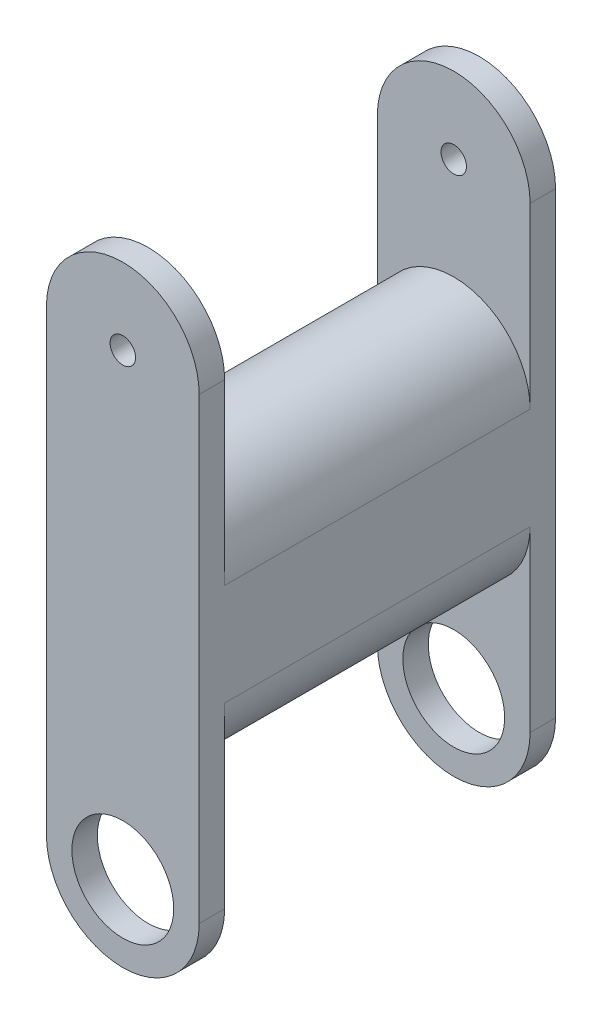
SolidWorks part; units mm, degrees
ref_plane "前视基准面" through (0, 0, 0) normal (0, 0, 1) x (1, 0, 0)
ref_plane "上视基准面" through (0, 0, 0) normal (0, 1, 0) x (1, 0, 0)
ref_plane "右视基准面" through (0, 0, 0) normal (1, 0, 0) x (0, 0, -1)
other "Configuration Table"
sketch "草图1" plane through (0, 0, 0) normal (0, 0, 1) x (1, 0, 0)
  line L0 (0, 0) -> (0, 98.1827) construction
  line L2 (-15, 90) -> (15, 90) construction
  line L3 (-15, 90) -> (-15, 0)
  line L4 (-15, 0) -> (15, 0) construction
  line L5 (15, 90) -> (15, 0)
  arc A0 (-15, 0) -> (15, 0) centre (0, 0) ccw
  arc A1 (15, 90) -> (-15, 90) centre (0, 90) ccw
  circle A2 centre (0, 0) radius 10
  circle A3 centre (0, 90) radius 2.5
  dimension "D3" = 20
  dimension "D4" = 5
  dimension "D1" = 90
  dimension "D2" = 30
extrude "凸台-拉伸1" add sketch "草图1" along normal blind 70
sketch "草图2" plane through (-15, 0, 0) normal (-1, 0, 0) x (0, 0, 1)
  line L0 (35, 108.1134) -> (35, -21.1946) construction
  line L1 (70, 90) -> (70, 0) construction
  line L2 (0, 90) -> (0, 0) construction
  line L4 (5, 20) -> (65, 20)
  line L5 (5, 20) -> (5, -20)
  line L6 (5, -20) -> (65, -20)
  line L7 (65, 20) -> (65, -20)
  line L8 (5, 120) -> (65, 120)
  line L9 (5, 120) -> (5, 70)
  line L10 (5, 70) -> (65, 70)
  line L11 (65, 120) -> (65, 70)
  dimension "D1" = 20
  dimension "D2" = 60
  dimension "D3" = 60
  dimension "D4" = 70
  dimension "D5" = 50
  dimension "D6" = 40
extrude "切除-拉伸1" cut sketch "草图2" against normal blind 70 contours L11 L10 L9 L8 | L6 L7 L4 L5
sketch "草图3" plane through (0, 0, 65) normal (0, 0, -1) x (-1, 0, 0)
  line L0 (0, 0) -> (0, 40) construction
  line L1 (15, 70) -> (15, 55)
  line L2 (-15, 70) -> (-15, 55)
  line L3 (-15, 35) -> (-15, 20)
  line L4 (15, 0) -> (15, 20)
  line L5 (15, 20) -> (-15, 20)
  line L6 (-15, 20) -> (-15, 0)
  line L7 (15, 0) -> (15, 20) construction
  line L8 (15, 20) -> (-15, 20)
  line L9 (-15, 20) -> (-15, 0) construction
  line L10 (-15, 90) -> (-15, 70)
  line L11 (-15, 70) -> (15, 70)
  line L12 (15, 70) -> (15, 90)
  line L13 (-15, 90) -> (-15, 70) construction
  line L14 (-15, 70) -> (15, 70)
  line L15 (15, 70) -> (15, 90) construction
  line L16 (0, 50) -> (0, 90) construction
  line L17 (15, 35) -> (15, 20)
  arc A0 (-15, 35) -> (15, 35) centre (0, 35) ccw
  arc A1 (15, 55) -> (-15, 55) centre (0, 55) ccw
  arc A2 (-15, 0) -> (15, 0) centre (0, 0) ccw
  arc A3 (-15, 0) -> (15, 0) centre (0, 0) ccw construction
  arc A4 (15, 90) -> (-15, 90) centre (0, 90) ccw
  arc A5 (15, 90) -> (-15, 90) centre (0, 90) ccw construction
  line M15 (15, 20) -> (-15, 20)
  dimension "D3" = 30
  dimension "D4" = 30
  dimension "D1" = 0
  dimension "D2" = 0
extrude "切除-拉伸2" cut sketch "草图3" along direction (0, 0, -1) on the side of the normal up to surface (60 mm away) contours A1 L1 L14 | A1 L14 L2 | A0 L3 L8 | A0 L17 M15
